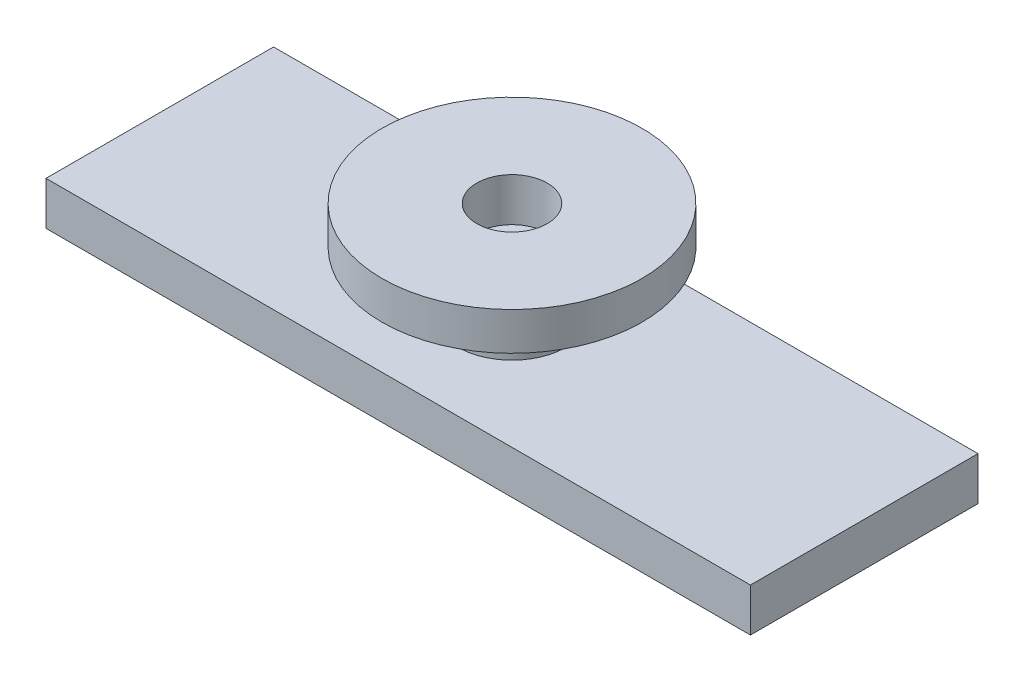
SolidWorks part; units mm, degrees
ref_plane "Plano frontal" through (0, 0, 0) normal (0, 0, 1) x (1, 0, 0)
ref_plane "Plano superior" through (0, 0, 0) normal (0, 1, 0) x (1, 0, 0)
ref_plane "Plano direito" through (0, 0, 0) normal (1, 0, 0) x (0, 0, -1)
sketch "Esboço1" plane through (0, 0, 0) normal (0, 1, 0) x (1, 0, 0)
  line L1 (-32.5, 10.5) -> (32.5, 10.5)
  line L2 (-32.5, 10.5) -> (-32.5, -10.5)
  line L3 (-32.5, -10.5) -> (32.5, -10.5)
  line L4 (32.5, 10.5) -> (32.5, -10.5)
  circle A1 centre (0, 0) radius 6.5
  dimension "D5" = 13
  dimension "D1" = 65
  dimension "D2" = 21
  dimension "D3" = 10.5
  dimension "D4" = 32.5
extrude "Ressalto-extrusão3" add sketch "Esboço1" along normal blind 4 contours L2 L1 L4 L3
sketch "Esboço3" plane through (0, 0, 0) normal (0, -1, 0) x (1, 0, 0)
sketch "Esboço5" plane through (0, 0, 0) normal (0, -1, 0) x (1, 0, 0)
  circle A0 centre (0, 0) radius 6.5
  dimension "D1" = 13
extrude "Corte-extrusão2" cut sketch "Esboço5" against normal blind 3
sketch "Esboço6" plane through (0, 3, 0) normal (0, -1, 0) x (1, 0, 0)
  circle A0 centre (0, 0) radius 3
  dimension "D1" = 6
extrude "Corte-extrusão3" cut sketch "Esboço6" against normal blind 4
sketch "Esboço7" plane through (0, 4, 0) normal (0, 1, 0) x (1, 0, 0)
  circle A0 centre (0, 0) radius 5
  dimension "D1" = 10
extrude "Ressalto-extrusão4" add sketch "Esboço7" along normal blind 5.5
sketch "Esboço8" plane through (0, 9.5, 0) normal (0, 1, 0) x (1, 0, 0)
  circle A0 centre (0, 0) radius 3.25
  dimension "D1" = 6.5
extrude "Corte-extrusão4" cut sketch "Esboço8" against normal blind 0.5
sketch "Esboço10" plane through (0, 4, 0) normal (0, -1, 0) x (1, 0, 0)
  circle A0 centre (0, 0) radius 3
extrude "Corte-extrusão5" cut sketch "Esboço10" against normal blind 3
sketch "Esboço11" plane through (0, 9.5, 0) normal (0, 1, 0) x (1, 0, 0)
  circle A0 centre (0, 0) radius 12
  circle A1 centre (0, 0) radius 3.25
  dimension "D1" = 24
  dimension "D2" = 6.5
extrude "Ressalto-extrusão5" add sketch "Esboço11" along normal blind 3.5
sketch "Esboço12" plane through (0, 9, 0) normal (0, 1, 0) x (1, 0, 0)
  circle A0 centre (0, 0) radius 1.5
  dimension "D1" = 3
extrude "Corte-extrusão6" cut sketch "Esboço12" against normal blind 5
